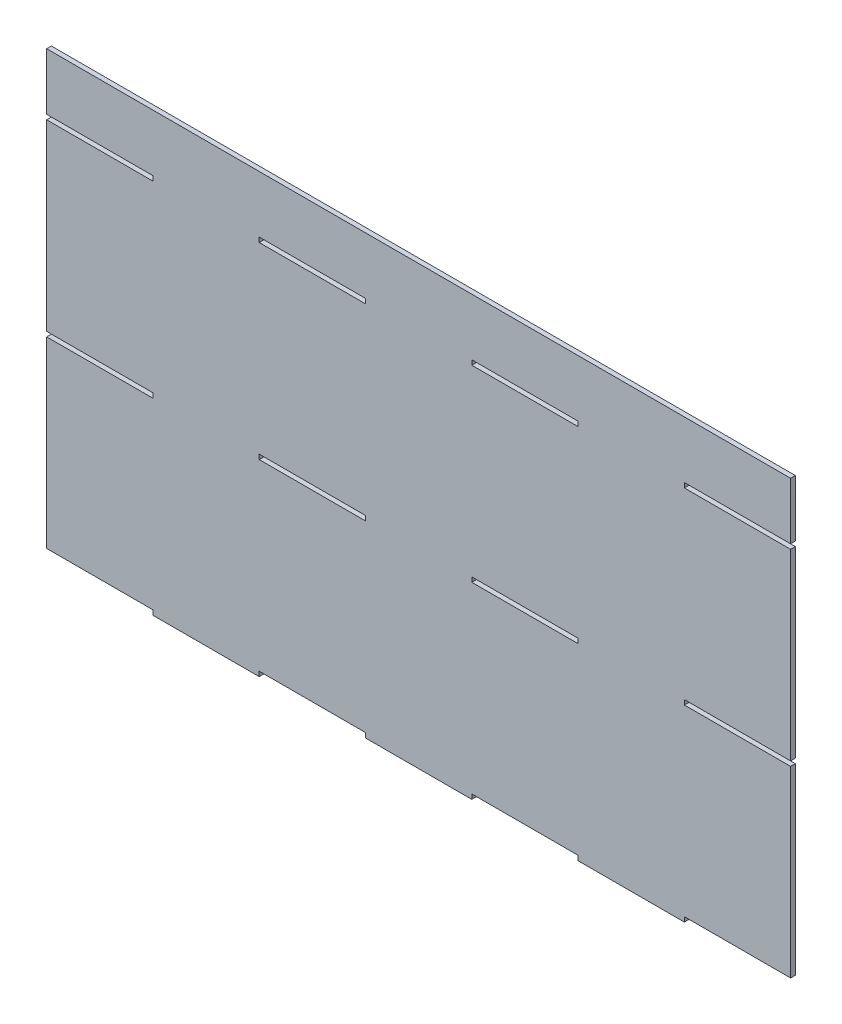
SolidWorks part; units mm, degrees
material "Acrylic (Medium-high impact)"
ref_plane "Front Plane" through (0, 0, 0) normal (0, 0, 1) x (1, 0, 0)
ref_plane "Top Plane" through (0, 0, 0) normal (0, 1, 0) x (1, 0, 0)
ref_plane "Right Plane" through (0, 0, 0) normal (1, 0, 0) x (0, 0, -1)
sketch "Sketch1" plane through (0, 0, 0) normal (0, 0, 1) x (1, 0, 0)
  line L1 (50.8998, -0.0125) -> (122.3283, -0.0125)
  line L6 (479.4712, 3.1625) -> (408.0426, 3.1625) construction
  line L7 (408.0426, -0.0125) -> (408.0426, 3.1625) construction
  line L8 (336.614, -0.0125) -> (336.614, 3.1625) construction
  line L9 (336.614, 3.1625) -> (265.1855, 3.1625) construction
  line L10 (265.1855, -0.0125) -> (265.1855, 3.1625) construction
  line L11 (193.7569, -0.0125) -> (193.7569, 3.1625) construction
  line L12 (193.7569, 3.1625) -> (122.3283, 3.1625) construction
  line L13 (122.3283, -0.0125) -> (122.3283, 3.1625) construction
  line L14 (50.8998, -0.0125) -> (50.8998, 3.1625) construction
  line L15 (50.8998, 3.1625) -> (-20.5288, 3.1625) construction
  line L16 (479.4712, 3.1625) -> (408.0426, 3.1625)
  line L17 (408.0426, -0.0125) -> (408.0426, 3.1625)
  line L18 (336.614, -0.0125) -> (336.614, 3.1625)
  line L19 (336.614, 3.1625) -> (265.1855, 3.1625)
  line L20 (265.1855, -0.0125) -> (265.1855, 3.1625)
  line L21 (193.7569, -0.0125) -> (193.7569, 3.1625)
  line L22 (193.7569, 3.1625) -> (122.3283, 3.1625)
  line L23 (122.3283, -0.0125) -> (122.3283, 3.1625)
  line L24 (50.8998, -0.0125) -> (50.8998, 3.1625)
  line L25 (50.8998, 3.1625) -> (-20.5288, 3.1625)
  line L26 (193.7569, -0.0125) -> (265.1855, -0.0125)
  line L27 (336.614, -0.0125) -> (408.0426, -0.0125)
  line L29 (-20.5288, 3.1625) -> (-20.5288, 126.3375)
  line L33 (479.4712, 294.0375) -> (479.4712, 255.8625)
  line L82 (479.4712, 294.0375) -> (166.4712, 294.0375) construction
  line L83 (479.4712, 294.0375) -> (166.4712, 294.0375)
  line L84 (166.4712, 294.0375) -> (-20.5288, 294.0375)
  line L85 (479.4712, 126.3375) -> (408.0426, 126.3375) construction
  line L86 (408.0426, 126.3375) -> (408.0426, 129.5125) construction
  line L87 (479.4712, 129.5125) -> (408.0426, 129.5125) construction
  line L88 (408.0426, 252.6875) -> (408.0426, 255.8625) construction
  line L89 (479.4712, 252.6875) -> (408.0426, 252.6875) construction
  line L90 (479.4712, 255.8625) -> (408.0426, 255.8625) construction
  line L91 (336.614, 126.3375) -> (336.614, 129.5125) construction
  line L92 (336.614, 126.3375) -> (265.1855, 126.3375) construction
  line L93 (265.1855, 126.3375) -> (265.1855, 129.5125) construction
  line L94 (336.614, 129.5125) -> (265.1855, 129.5125) construction
  line L95 (336.614, 252.6875) -> (336.614, 255.8625) construction
  line L96 (336.614, 252.6875) -> (265.1855, 252.6875) construction
  line L97 (265.1855, 252.6875) -> (265.1855, 255.8625) construction
  line L98 (336.614, 255.8625) -> (265.1855, 255.8625) construction
  line L99 (193.7569, 126.3375) -> (193.7569, 129.5125) construction
  line L100 (193.7569, 126.3375) -> (122.3283, 126.3375) construction
  line L101 (193.7569, 129.5125) -> (122.3283, 129.5125) construction
  line L102 (122.3283, 126.3375) -> (122.3283, 129.5125) construction
  line L103 (193.7569, 252.6875) -> (193.7569, 255.8625) construction
  line L104 (193.7569, 252.6875) -> (122.3283, 252.6875) construction
  line L105 (122.3283, 252.6875) -> (122.3283, 255.8625) construction
  line L106 (193.7569, 255.8625) -> (122.3283, 255.8625) construction
  line L107 (50.8998, 126.3375) -> (50.8998, 129.5125) construction
  line L108 (50.8998, 126.3375) -> (-20.5288, 126.3375) construction
  line L109 (50.8998, 129.5125) -> (-20.5288, 129.5125) construction
  line L110 (50.8998, 252.6875) -> (50.8998, 255.8625) construction
  line L111 (50.8998, 252.6875) -> (-20.5288, 252.6875) construction
  line L112 (50.8998, 255.8625) -> (-20.5288, 255.8625) construction
  line L113 (479.4712, 126.3375) -> (408.0426, 126.3375)
  line L114 (408.0426, 126.3375) -> (408.0426, 129.5125)
  line L115 (479.4712, 129.5125) -> (408.0426, 129.5125)
  line L116 (408.0426, 252.6875) -> (408.0426, 255.8625)
  line L117 (479.4712, 252.6875) -> (408.0426, 252.6875)
  line L118 (479.4712, 255.8625) -> (408.0426, 255.8625)
  line L119 (336.614, 126.3375) -> (336.614, 129.5125)
  line L120 (336.614, 126.3375) -> (265.1855, 126.3375)
  line L121 (265.1855, 126.3375) -> (265.1855, 129.5125)
  line L122 (336.614, 129.5125) -> (265.1855, 129.5125)
  line L123 (336.614, 252.6875) -> (336.614, 255.8625)
  line L124 (336.614, 252.6875) -> (265.1855, 252.6875)
  line L125 (265.1855, 252.6875) -> (265.1855, 255.8625)
  line L126 (336.614, 255.8625) -> (265.1855, 255.8625)
  line L127 (193.7569, 126.3375) -> (193.7569, 129.5125)
  line L128 (193.7569, 126.3375) -> (122.3283, 126.3375)
  line L129 (193.7569, 129.5125) -> (122.3283, 129.5125)
  line L130 (122.3283, 126.3375) -> (122.3283, 129.5125)
  line L131 (193.7569, 252.6875) -> (193.7569, 255.8625)
  line L132 (193.7569, 252.6875) -> (122.3283, 252.6875)
  line L133 (122.3283, 252.6875) -> (122.3283, 255.8625)
  line L134 (193.7569, 255.8625) -> (122.3283, 255.8625)
  line L135 (50.8998, 126.3375) -> (50.8998, 129.5125)
  line L136 (50.8998, 126.3375) -> (-20.5288, 126.3375)
  line L137 (50.8998, 129.5125) -> (-20.5288, 129.5125)
  line L138 (50.8998, 252.6875) -> (50.8998, 255.8625)
  line L139 (50.8998, 252.6875) -> (-20.5288, 252.6875)
  line L140 (50.8998, 255.8625) -> (-20.5288, 255.8625)
  line L141 (479.4712, 252.6875) -> (479.4712, 129.5125)
  line L142 (479.4712, 126.3375) -> (479.4712, 3.1625)
  line L143 (-20.5288, 255.8625) -> (-20.5288, 294.0375)
  line L144 (-20.5288, 129.5125) -> (-20.5288, 252.6875)
  point P3 (0, 302.3532)
extrude "Boss-Extrude1" add sketch "Sketch1" along normal blind 3.175
